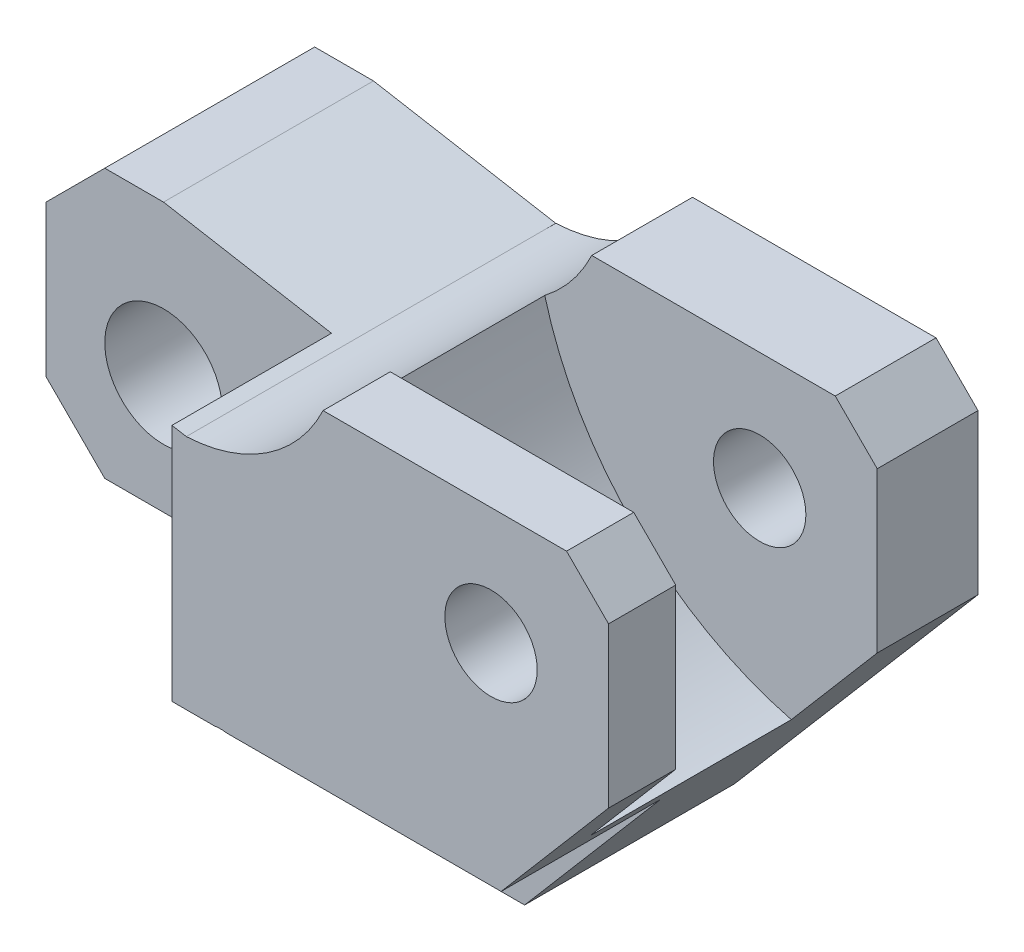
SolidWorks part; units mm, degrees
material "AISI 304"
ref_plane "Plan de face" through (0, 0, 0) normal (0, 0, 1) x (1, 0, 0)
ref_plane "Plan de dessus" through (0, 0, 0) normal (0, 1, 0) x (1, 0, 0)
ref_plane "Plan de droite" through (0, 0, 0) normal (1, 0, 0) x (0, 0, -1)
sketch "Esquisse1" plane through (0, 0, 0) normal (0, 0, 1) x (1, 0, 0)
  line L15 (69.0555, 42.5858) -> (98.0555, 42.5858)
  line L16 (98.0555, 42.5858) -> (103.0555, 37.5858)
  line L17 (103.0555, 37.5858) -> (103.0555, 18.5858)
  line L20 (103.0555, 18.5858) -> (74.0555, -15.4142)
  line L24 (31.0555, 35.5858) -> (52.7651, 31.7578)
  line L25 (31.0555, 35.5858) -> (24.0555, 35.5858)
  line L26 (24.0555, 35.5858) -> (17.0555, 28.5858)
  line L27 (17.0555, 28.5858) -> (17.0555, 10.5858)
  line L28 (17.0555, 10.5858) -> (24.0555, 3.5858)
  line L30 (24.0555, 3.5858) -> (56.0555, 3.5858)
  line L32 (74.0555, -15.4142) -> (68.3525, -15.4142)
  arc A4 (69.0555, 42.5858) -> (52.7651, 31.7578) centre (51.8932, 50.7378) cw
  arc A5 (56.0555, 3.5858) -> (61.7972, -1.9629) centre (56.8345, -1.3532) cw
  arc A7 (61.7972, -1.9629) -> (68.3525, -15.4142) centre (90.2614, 3.5858) ccw
  point P7 (90.2614, 3.5858)
  point P11 (71.204, -15.4142)
  dimension "D8" = 7
  dimension "D9" = 5
  dimension "D6" = 19
  dimension "D14" = 32
  dimension "D15" = 19
  dimension "D10" = 58
  dimension "D12" = 29
  dimension "D2" = 45
  dimension "D3" = 5
  dimension "D4" = 24
  dimension "D5" = 29
  dimension "D7" = 45
  dimension "D11" = 86
  dimension "D13" = 19
  dimension "D16" = 29
  dimension "D19" = 7
  dimension "D20" = 14
  dimension "D21" = 10
extrude "Boss.-Extru.1" add sketch "Esquisse1" along normal blind 44
sketch "Esquisse2" plane through (0, 0, 44) normal (0, 0, 1) x (1, 0, 0)
  line L0 (17.0555, 28.5858) -> (17.0555, 10.5858) construction
  line L1 (24.0555, 3.5858) -> (56.0555, 3.5858) construction
  circle A0 centre (31.0555, 17.5858) radius 7
  dimension "D1" = 14
  dimension "D2" = 14
  dimension "D3" = 14
extrude "Enlèv. mat.-Extru.1" cut sketch "Esquisse2" against normal blind 44
sketch "Esquisse3" plane through (0, 0, 44) normal (0, 0, 1) x (1, 0, 0)
  line L0 (17.0555, 28.5858) -> (17.0555, 10.5858)
  line L1 (17.0555, 10.5858) -> (24.0555, 3.5858)
  line L2 (24.0555, 3.5858) -> (51.0555, 3.5858)
  line L3 (24.0555, 3.5858) -> (56.0555, 3.5858) construction
  line L4 (51.0555, 3.5858) -> (51.0555, 32.0592)
  line L5 (52.7651, 31.7578) -> (31.0555, 35.5858) construction
  line L6 (51.0555, 32.0592) -> (31.0555, 35.5858)
  line L7 (31.0555, 35.5858) -> (24.0555, 35.5858)
  line L8 (31.0555, 35.5858) -> (24.0555, 35.5858) construction
  line L9 (24.0555, 35.5858) -> (17.0555, 28.5858)
  dimension "D1" = 34
extrude "Enlèv. mat.-Extru.2" cut sketch "Esquisse3" against normal blind 19
sketch "Esquisse4" plane through (0, 0, 44) normal (0, 0, 1) x (1, 0, 0)
  line L0 (103.0555, 18.5858) -> (103.0555, 37.5858) construction
  line L1 (98.0555, 42.5858) -> (69.0555, 42.5858) construction
  circle A0 centre (89.0555, 28.5858) radius 5.5
  dimension "D1" = 11
  dimension "D2" = 14
  dimension "D3" = 14
extrude "Enlèv. mat.-Extru.3" cut sketch "Esquisse4" against normal blind 50
sketch "Esquisse10" plane through (0, 0, 44) normal (0, 0, 1) x (1, 0, 0)
  line L0 (56.0555, 3.5858) -> (90.2614, 3.5858)
  line L1 (74.0555, -15.4142) -> (103.0555, 18.5858) construction
  line L2 (90.2614, 3.5858) -> (74.0555, -15.4142)
  line L3 (74.0555, -15.4142) -> (68.3525, -15.4142)
  arc A0 (61.7972, -1.9629) -> (56.0555, 3.5858) centre (56.8345, -1.3532) ccw construction
  arc A1 (56.0555, 3.5858) -> (61.7972, -1.9629) centre (56.0555, -2.1592) cw
  arc A2 (61.7972, -1.9629) -> (68.3525, -15.4142) centre (90.2614, 3.5858) ccw
  dimension "D1" = 19
extrude "Enlèv. mat.-Extru.5" cut sketch "Esquisse10" against normal blind 19
sketch "Esquisse11" plane through (0, 0, 44) normal (0, 0, 1) x (1, 0, 0)
  line L0 (103.0555, 37.5858) -> (103.0555, 50.3291)
  line L1 (103.0555, 18.5858) -> (103.0555, 37.5858) construction
  line L2 (103.0555, 37.5858) -> (98.0555, 42.5858) construction
sketch "Esquisse13" plane through (0, 0, 44) normal (0, 0, 1) x (1, 0, 0)
  line L0 (103.0555, 37.5858) -> (103.0555, 50.3291) construction
  line L1 (90.2614, 3.5858) -> (103.0555, 18.5858) construction
  line L2 (98.0555, 42.5858) -> (69.0555, 42.5858) construction
  line L3 (69.0555, 42.5858) -> (98.0555, 42.5858)
  line L4 (98.0555, 42.5858) -> (103.0555, 37.5858)
  line L5 (103.0555, 37.5858) -> (103.0555, 18.5858)
  line L6 (103.0555, 18.5858) -> (92.8202, 6.5858)
  arc A0 (63.4564, 35.6616) -> (92.8202, 6.5858) centre (103.0555, 46.2877) ccw
  arc A1 (52.7651, 31.7578) -> (69.0555, 42.5858) centre (51.8932, 50.7378) ccw construction
  arc A2 (63.4564, 35.6616) -> (69.0555, 42.5858) centre (51.8932, 50.7378) ccw
  dimension "D2" = 41
  dimension "D1" = 36
extrude "Enlèv. mat.-Extru.8" cut sketch "Esquisse13" against normal blind 32
sketch "Esquisse14" plane through (0, 0, 44) normal (0, 0, 1) x (1, 0, 0)
  line L0 (92.8202, 6.5858) -> (103.0555, 18.5858)
  line L1 (103.0555, 18.5858) -> (103.0555, 37.5858)
  line L2 (103.0555, 37.5858) -> (98.0555, 42.5858)
  line L3 (98.0555, 42.5858) -> (69.0555, 42.5858)
  line L4 (103.0555, 37.5858) -> (103.0555, 50.3291) construction
  line L5 (90.2614, 3.5858) -> (92.8202, 6.5858) construction
  arc A0 (63.4564, 35.6616) -> (92.8202, 6.5858) centre (103.0555, 46.2877) ccw
  arc A1 (63.4564, 35.6616) -> (69.0555, 42.5858) centre (51.8932, 50.7378) ccw
  dimension "D2" = 41
  dimension "D1" = 36
extrude "Boss.-Extru.3" add sketch "Esquisse14" against normal blind 8
sketch "Esquisse15" plane through (0, 0, 44) normal (0, 0, 1) x (1, 0, 0)
  circle A0 centre (89.0555, 28.5858) radius 5.5
extrude "Enlèv. mat.-Extru.9" cut sketch "Esquisse15" against normal blind 44
